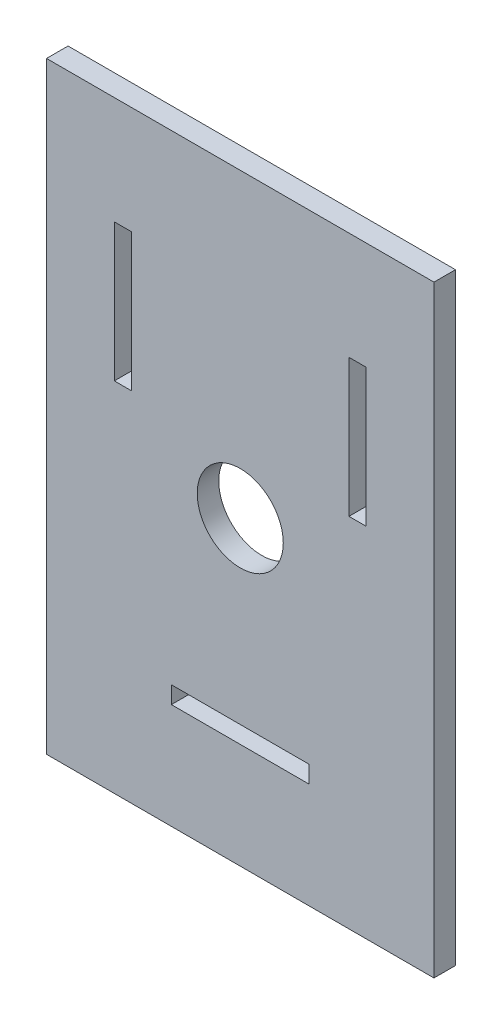
SolidWorks part; units mm, degrees
material "Alloy Steel"
ref_plane "Front Plane" through (0, 0, 0) normal (0, 0, 1) x (1, 0, 0)
ref_plane "Top Plane" through (0, 0, 0) normal (0, 1, 0) x (1, 0, 0)
ref_plane "Right Plane" through (0, 0, 0) normal (1, 0, 0) x (0, 0, -1)
sketch "BaseS" plane through (0, 0, 0) normal (0, 0, 1) x (1, 0, 0)
  line L1 (-9, 14) -> (9, 14)
  line L2 (-9, 14) -> (-9, -14)
  line L3 (-9, -14) -> (9, -14)
  line L4 (9, 14) -> (9, -14)
  line L5 (-9, 14) -> (9, -14) construction
  line L6 (-9, -14) -> (9, 14) construction
  point P0 (0, 0)
  dimension "D1" = 18
  dimension "D2" = 28
extrude "BASE" add sketch "BaseS" against normal blind 1
sketch "NeutralS" plane through (0, 0, 0) normal (0, 0, 1) x (1, 0, 0)
  line L1 (5.05, 9) -> (5.85, 9)
  line L2 (5.05, 9) -> (5.05, 2.6)
  line L3 (5.05, 2.6) -> (5.85, 2.6)
  line L4 (5.85, 9) -> (5.85, 2.6)
  line L5 (5.05, 9) -> (5.85, 2.6) construction
  line L6 (5.05, 2.6) -> (5.85, 9) construction
  point P0 (5.45, 5.8)
  dimension "D1" = 6.4
  dimension "D2" = 0.8
  dimension "D3" = 5.45
  dimension "D4" = 5.8
extrude "NEUTRAL" cut sketch "NeutralS" against normal blind 1.6
mirror "LINE HM" about plane through (0, 0, 0) normal (1, 0, 0) of "NEUTRAL"
sketch "ScrewAccessS" plane through (0, 0, 0) normal (0, 0, 1) x (1, 0, 0)
  circle A0 centre (0, 0) radius 2
  dimension "D1" = 4
extrude "SCREW ACCESS" cut sketch "ScrewAccessS" against normal through all
sketch "GroundS" plane through (0, 0, 0) normal (0, 0, 1) x (1, 0, 0)
  line L0 (0, -8.7) -> (0, 0) construction
  line L1 (-3.2, -8.3) -> (3.2, -8.3)
  line L2 (-3.2, -8.3) -> (-3.2, -9.1)
  line L3 (-3.2, -9.1) -> (3.2, -9.1)
  line L4 (3.2, -8.3) -> (3.2, -9.1)
  line L5 (-3.2, -8.3) -> (3.2, -9.1) construction
  line L6 (-3.2, -9.1) -> (3.2, -8.3) construction
  point P0 (0, -8.7)
  dimension "D1" = 6.4
  dimension "D2" = 0.8
  dimension "D3" = 14.5
extrude "GROUND" cut sketch "GroundS" against normal blind 1.6
